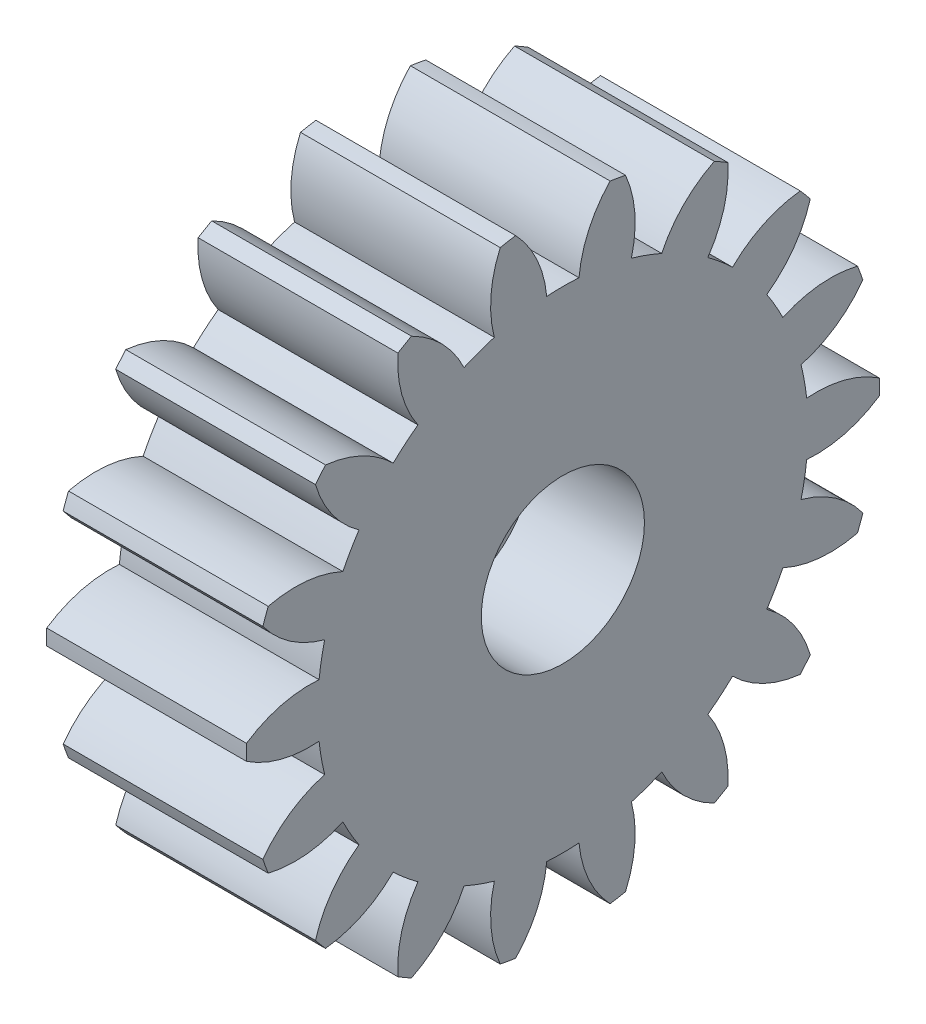
SolidWorks part; units mm, degrees
ref_plane "Plane1" through (0, 0, 0) normal (0, 0, 1) x (1, 0, 0)
ref_plane "Plane2" through (0, 0, 0) normal (0, 1, 0) x (1, 0, 0)
ref_plane "Plane3" through (0, 0, 0) normal (1, 0, 0) x (0, 0, -1)
other "Configuration Table"
sketch "HoldingSke" plane through (0, 0, 0) normal (0, 1, 0) x (1, 0, 0)
  line L0 (0, 0) -> (0.8454, -0.2747)
  line L1 (-15, 0) -> (100, 0) construction
  line L2 (0, 0) -> (-2.1039, 2.3779)
  line L3 (0, 0) -> (-11.863, 4.5341)
  line L4 (0, 0) -> (8.2133, 2.6687)
  line L5 (0, 0) -> (-46.8476, -17.4728)
  line L6 (0, 0) -> (-5.8856, -3.9711)
  line L7 (-2.1039, 2.3779) -> (8.6586, 51.2059)
  line L8 (-76.2, 54.61) -> (-75.7, 54.61)
  line L9 (-71.009, 38.7566) -> (-53.1078, 45.2721)
  line L10 (-76.2, 71.12) -> (104.1128, 71.12)
  line L11 (0, 0) -> (-7.1, 0)
  line L12 (-76.2, 101.6) -> (-76.158, 101.6)
  line L13 (24.9733, 27.94) -> (52.9518, 28.4284)
  line L14 (24.9733, 27.94) -> (24.9743, 27.94)
  line L15 (24.9733, 27.94) -> (100.4006, 29.5858)
  line L16 (-63.627, -1.125) -> (-12.827, -1.125)
  circle A0 centre (0, 0) radius 1.5
  circle A1 centre (0, 0) radius 8.7177
  circle A2 centre (0, 0) radius 37.5
  circle A3 centre (0, 0) radius 1.5
  dimension "MHD" = 17.4355
  dimension "Hub_dia" = 75
  dimension "Bore" = 3
  dimension "MBD" = 3
  dimension "Num_teeth" = 18
  dimension "Pitch" = 0.8889
  dimension "Overall_len" = 50
  dimension "Show_teeth" = 18
  dimension "Thickness" = 7.1
  dimension "OAL" = 50.0001
  dimension "T_dim" = 0.5
  dimension "Ap" = 20
  dimension "H" = 19.05
  dimension "Pitch_radius" = 180.3128
  dimension "Width" = 7.1
  dimension "Backlash" = 0.042
  dimension "Addendum_fac" = 1
  dimension "Dedendum_fac" = 1.25
  dimension "Clearance_fac" = 0.25
  dimension "Dedendum_add" = 0.001
  dimension "Module" = 1.125
sketch "BasProSke" plane through (0, 0, 0) normal (0, 1, 0) x (1, 0, 0)
  line L0 (-10, 0) -> (60, 0) construction
  line L1 (0, 0) -> (0, 11.25)
  line L2 (0, 0) -> (7.1, 0)
  line L3 (7.1, 0) -> (7.1, 11.25)
  line L4 (7.1, 11.25) -> (0, 11.25)
  dimension "Thickness" = 7.1
  dimension "Diameter" = 22.5
revolve "Base-Revolve" add sketch "BasProSke" angle 360 about L0
sketch "TooCutSke" plane through (0, 0, 0) normal (1, 0, 0) x (0, 0, -1)
  line L1 (0, 0) -> (0, 107) construction
  line L2 (0, 0) -> (-0.9559, 10.0798) construction
  line L3 (0, 0) -> (-3.5051, 19.8786) construction
  line L4 (-0.9559, 10.0798) -> (-1.7526, 9.9393) construction
  arc A0 (0.5734, 8.6989) -> (-0.5734, 8.6989) centre (0, 0) ccw
  arc A1 (1.7004, 11.1464) -> (-1.7004, 11.1464) centre (0, 0) ccw
  circle A2 centre (0, 0) radius 10.125 construction
  circle A3 centre (0, 0) radius 9.5144 construction
  arc A4 (-0.5734, 8.6989) -> (-1.7004, 11.1464) centre (-4.6061, 8.3251) ccw
  arc A5 (1.7004, 11.1464) -> (0.5734, 8.6989) centre (4.6061, 8.3251) ccw
  dimension "Root_dia" = 17.4355
  dimension "Overcut_dia" = 22.5508
  dimension "Pitch_dia" = 20.25
  dimension "Base_dia" = 19.0288
  dimension "Flank_rad" = 4.05
  dimension "Half_ang" = 10
  dimension "Half_CT" = 0.809
extrude "ToothCut" cut sketch "TooCutSke" along normal through all
fillet "Breaks" [suppressed] radius 0.0225
fillet "RootFillets" [suppressed] radius 0.2822
pattern_circular "TeethCuts" count 18 every 20 about axis through (-10, 0, 0) along (1, 0, 0) of "ToothCut", "RootFillets", "Breaks"
sketch "HubNeaOneSke" plane through (0, 0, 0) normal (-1, 0, 0) x (0, 0, 1)
  circle A0 centre (0, 0) radius 8.7177
  dimension "Diameter" = 17.4355
extrude "HubNearOne" [suppressed] add sketch "HubNeaOneSke" along normal blind 42.9001
sketch "HubNeaBotSke" plane through (0, 0, 0) normal (-1, 0, 0) x (0, 0, 1)
  circle A0 centre (0, 0) radius 8.7177
  dimension "Diameter" = 17.4355
extrude "HubNearBoth" [suppressed] add sketch "HubNeaBotSke" along normal blind 21.45
ref_plane "FarPln" through (7.1, 0, 0) normal (1, 0, 0) x (0, 0, -1)
sketch "HubFarSke" plane through (7.1, 0, 0) normal (1, 0, 0) x (0, 0, -1)
  circle A0 centre (0, 0) radius 8.7177
  dimension "Diameter" = 17.4355
extrude "HubFar" [suppressed] add sketch "HubFarSke" along normal blind 21.45
sketch "BorSke" plane through (0, 0, 0) normal (1, 0, 0) x (0, 0, -1)
  circle A0 centre (0, 0) radius 1.5
  dimension "Diameter" = 3
extrude "Bore" cut sketch "BorSke" along normal mid plane 100.0001
sketch "KeySke" plane through (0, 0, 0) normal (1, 0, 0) x (0, 0, -1)
  line L0 (-0.6, 0) -> (-0.6, 2)
  line L1 (-0.6, 2) -> (0.6, 2)
  line L2 (0.6, 2) -> (0.6, 0)
  line L3 (0, 0) -> (0, 34) construction
  line L4 (-0.6, 0) -> (0.6, 0)
  dimension "Offset" = 2
  dimension "Width" = 1.2
extrude "Keyway" [suppressed] cut sketch "KeySke" along normal mid plane 100.0001
pattern_circular "Keyway2" [suppressed] count 2 every 90 about axis through (-10, 0, 0) along (1, 0, 0)
sketch "Sketch1" plane through (7.1, 0, 0) normal (1, 0, 0) x (0, 0, -1)
  circle A0 centre (0, 0) radius 2.9
  dimension "D1" = 5.8
extrude "Cut-Extrude1" cut sketch "Sketch1" against normal blind 4
equation "' \"Module@HoldingSke\" = 6.35"
equation "' \"Num_teeth@HoldingSke\" = 12"
equation "' \"Ap@HoldingSke\" =  20"
equation "' \"Ap@HoldingSke\" = 20"
equation "' \"Width@HoldingSke\" = 0.5 * 25.4"
equation "' \"Hub_dia@HoldingSke\"= 1 * 25.4"
equation "' \"Hub_dia@HoldingSke\" = 1 * 25.4"
equation "' \"Overall_len@HoldingSke\" = 1.0 * 25.4"
equation "' \"Bore@HoldingSke\" = 0.75 * 25.4"
equation "' \"T_dim@HoldingSke\" = 0.1 * 25.4"
equation "' \"Width@KeySke\" = 0.25 * 25.4"
equation "' \"Show_teeth@HoldingSke\" = 13"
equation "' \"Backlash@HoldingSke\" = 0.009 * 25.4"
equation "' \"Addendum_fac@HoldingSke\" = 1.0"
equation "' \"Dedendum_fac@HoldingSke\" = 1.25"
equation "' \"Dedendum_add@HoldingSke\" = 0.00005 * 25.4"
equation "' \"Clearance_fac@HoldingSke\" = 0.25"
equation "\"Pitch@HoldingSke\" = 1 / \"Module@HoldingSke\""
equation "\"Overcut_dia@TooCutSke\" = (\"Num_teeth@HoldingSke\" + 2 * \"Addendum_fac@HoldingSke\") / \"Pitch@HoldingSke\" + 0.002 * 25.4"
equation "\"Pitch_dia@TooCutSke\" = \"Num_teeth@HoldingSke\" / \"Pitch@HoldingSke\""
equation "\"Base_dia@TooCutSke\" = \"Num_teeth@HoldingSke\" / \"Pitch@HoldingSke\" * cos((\"Ap@HoldingSke\"  * 3.14159265 / 180))"
equation "\"Root_dia@TooCutSke\" = (\"Num_teeth@HoldingSke\" + 2) / \"Pitch@HoldingSke\" - 2 * (\"Addendum_fac@HoldingSke\" + \"Dedendum_fac@HoldingSke\") / \"Pitch@HoldingSke\" - \"Dedendum_add@HoldingSke\" * 2"
equation "\"Half_ang@TooCutSke\" = 180 / \"Num_teeth@HoldingSke\""
equation "\"Half_CT@TooCutSke\" = \"Num_teeth@HoldingSke\" / \"Pitch@HoldingSke\" * sin((3.14159265 / 2 / \"Num_teeth@HoldingSke\")) / 2 - 7 * \"Backlash@HoldingSke\" / 4"
equation "\"Flank_rad@TooCutSke\" = \"Num_teeth@HoldingSke\" / \"Pitch@HoldingSke\" / 5"
equation "\"Radius@RootFillets\" = \"Clearance_fac@HoldingSke\" / \"Pitch@HoldingSke\" + \"Dedendum_add@HoldingSke\""
equation "\"Break_rad@Breaks\" = 0.02 / \"Pitch@HoldingSke\""
equation "\"Thickness@HoldingSke\" = \"Width@HoldingSke\""
equation "\"OAL@HoldingSke\" = \"Thickness@HoldingSke\""
equation "\"MHD@HoldingSke\" = (\"Num_teeth@HoldingSke\" + 2) / \"Pitch@HoldingSke\" - 2 * (\"Addendum_fac@HoldingSke\" + \"Dedendum_fac@HoldingSke\")  / \"Pitch@HoldingSke\" - \"Dedendum_add@HoldingSke\" * 2"
equation "\"MBD@HoldingSke\" = (\"Num_teeth@HoldingSke\" + 2) / \"Pitch@HoldingSke\" - 2 * (\"Addendum_fac@HoldingSke\" + \"Dedendum_fac@HoldingSke\")  / \"Pitch@HoldingSke\" - \"Dedendum_add@HoldingSke\" * 2 - 0.002 * 25.4"
equation "\"MHD@HoldingSke\" = ((sgn( \"MHD@HoldingSke\" - \"Hub_dia@HoldingSke\" )-1)*( \"MHD@HoldingSke\" - \"Hub_dia@HoldingSke\" ))/-2+ \"Hub_dia@HoldingSke\""
equation "\"MBD@HoldingSke\" = ((sgn( \"MBD@HoldingSke\" - \"Bore@HoldingSke\" )-1)*( \"MBD@HoldingSke\" - \"Bore@HoldingSke\" ))/-2+ \"Bore@HoldingSke\""
equation "\"OAL@HoldingSke\" = ((sgn( \"OAL@HoldingSke\" - \"Overall_len@HoldingSke\" )+1)*( \"OAL@HoldingSke\" - \"Overall_len@HoldingSke\" ))/2 + \"Overall_len@HoldingSke\" + 0.000002 * 25.4"
equation "\"Num_teeth@TeethCuts\" = int( \"Show_teeth@HoldingSke\" ) + 1"
equation "\"Num_teeth@TeethCuts\" = ((sgn( \"Num_teeth@TeethCuts\" - \"Num_teeth@HoldingSke\" )-1)*( \"Num_teeth@TeethCuts\" - \"Num_teeth@HoldingSke\" ))/-2+ \"Num_teeth@HoldingSke\""
equation "\"Num_teeth@TeethCuts\" = ((sgn( \"Num_teeth@TeethCuts\" - 2.0)+1)*( \"Num_teeth@TeethCuts\" - 2.0))/2 +2.0"
equation "\"Angle@TeethCuts\" = 360.0 / \"Num_teeth@HoldingSke\""
equation "\"Diameter@BasProSke\" = (\"Num_teeth@HoldingSke\" + 2 * \"Addendum_fac@HoldingSke\") / \"Pitch@HoldingSke\""
equation "\"Thickness@BasProSke\"  = \"Thickness@HoldingSke\""
equation "' \"Fillet_rad@BasProSke\" =  \"Thickness@HoldingSke\" * 0.05"
equation "' \"Fillet_rad@BasProSke\" = \"Thickness@HoldingSke\" * 0.05"
equation "\"MHD@HoldingSke\" = ((sgn( \"MHD@HoldingSke\" - \"Root_dia@TooCutSke\" )-1)*( \"MHD@HoldingSke\" - \"Root_dia@TooCutSke\" ))/-2+ \"Root_dia@TooCutSke\""
equation "\"Diameter@HubNeaOneSke\" = \"MHD@HoldingSke\""
equation "\"Length@HubNearOne\" = \"OAL@HoldingSke\" - \"Thickness@BasProSke\""
equation "\"Diameter@HubNeaBotSke\" = \"MHD@HoldingSke\""
equation "\"Length@HubNearBoth\" = ( \"OAL@HoldingSke\" - \"Thickness@BasProSke\" ) / 2.0"
equation "\"Thickness@FarPln\" = \"Thickness@BasProSke\""
equation "\"Diameter@HubFarSke\" = \"MHD@HoldingSke\""
equation "\"Length@HubFar\" = ( \"OAL@HoldingSke\" - \"Thickness@BasProSke\" ) / 2.0"
equation "\"Diameter@BorSke\" = \"MBD@HoldingSke\""
equation "\"D1@Bore\" = \"OAL@HoldingSke\" * 2.0"
equation "\"D1@Keyway\" = \"OAL@HoldingSke\" * 2.0"
equation "\"Offset@KeySke\" = \"T_dim@HoldingSke\" + \"MBD@HoldingSke\" / 2.0"
